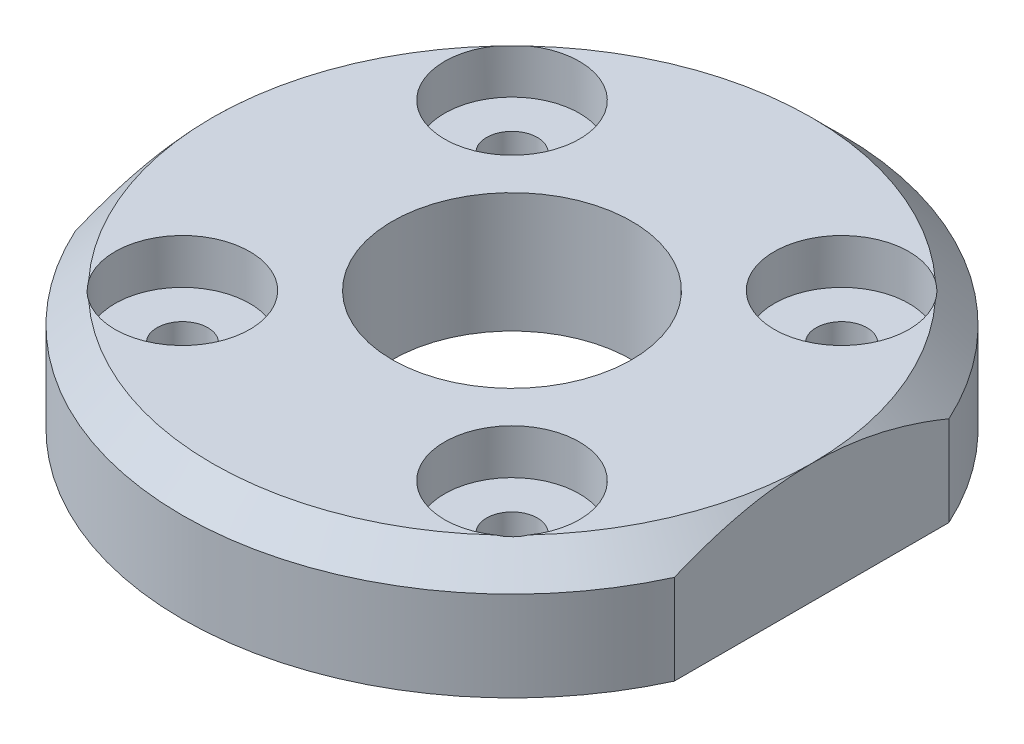
SolidWorks part; units mm, degrees
material "AISI 304"
ref_plane "前视基准面" through (0, 0, 0) normal (0, 0, 1) x (1, 0, 0)
ref_plane "上视基准面" through (0, 0, 0) normal (0, 1, 0) x (1, 0, 0)
ref_plane "右视基准面" through (0, 0, 0) normal (1, 0, 0) x (0, 0, -1)
sketch "Sketch1" plane through (0, 0, 0) normal (0, 1, 0) x (1, 0, 0)
  circle A0 centre (0, 0) radius 22
  circle A1 centre (0, 0) radius 8
  dimension "D1" = 44
  dimension "D2" = 16
extrude "Extrude1" add sketch "Sketch1" along normal blind 8
chamfer "Chamfer1" distance 2 angle 45 1 edges at (0, 8, 22)
sketch "Sketch2" plane through (0, 8, 0) normal (0, 1, 0) x (1, 0, 0)
  line L1 (11, -11) -> (-11, -11) construction
  line L2 (11, -11) -> (11, 11) construction
  line L3 (11, 11) -> (-11, 11) construction
  line L4 (-11, -11) -> (-11, 11) construction
  line L5 (11, -11) -> (-11, 11) construction
  line L6 (11, 11) -> (-11, -11) construction
  point P0 (0, 0)
  dimension "D1" = 22
hole_wizard "CBORE for M3 Hex Head Bolt1" positions "3DSketch1" profile "Sketch3" counterbore size "M3" standard "GB"
sketch3d "3DSketch1"
  point P0 (-11, 8, -11)
  point P3 (11, 8, -11)
  point P6 (11, 8, 11)
  point P9 (-11, 8, 11)
sketch "Sketch3" plane through (-11, 8, -11) normal (1, 0, 0) x (0, 0, 1)
  line L0 (0, 0) -> (0, 11.1215)
  line L1 (0, 11.1215) -> (1.7, 10.1)
  line L2 (1.7, 10.1) -> (1.7, 3)
  line L3 (1.7, 3) -> (4.5, 3)
  line L4 (4.5, 3) -> (4.5, 0)
  line L5 (4.5, 0) -> (0, 0)
  line L10 (0, 11.1215) -> (-1.7, 10.1) construction
  line L11 (0, -6.35) -> (0, 107.95) construction
  dimension "孔直径" = 3.4
  dimension "孔深度" = 10.1
  dimension "柱形沉头孔直径" = 9
  dimension "柱形沉头孔深度" = 3
  dimension "导头角度" = 118
sketch "Sketch4" plane through (0, 0, 0) normal (0, -1, 0) x (1, 0, 0)
  line L1 (20, -27.1326) -> (-20, -27.1326)
  line L2 (20, -27.1326) -> (20, 27.1326)
  line L3 (20, 27.1326) -> (-20, 27.1326)
  line L4 (-20, -27.1326) -> (-20, 27.1326)
  line L5 (20, -27.1326) -> (-20, 27.1326) construction
  line L6 (20, 27.1326) -> (-20, -27.1326) construction
  point P0 (0, 0)
  dimension "D1" = 20
extrude "Extrude2" cut sketch "Sketch4" against normal blind 30 flip side to cut
